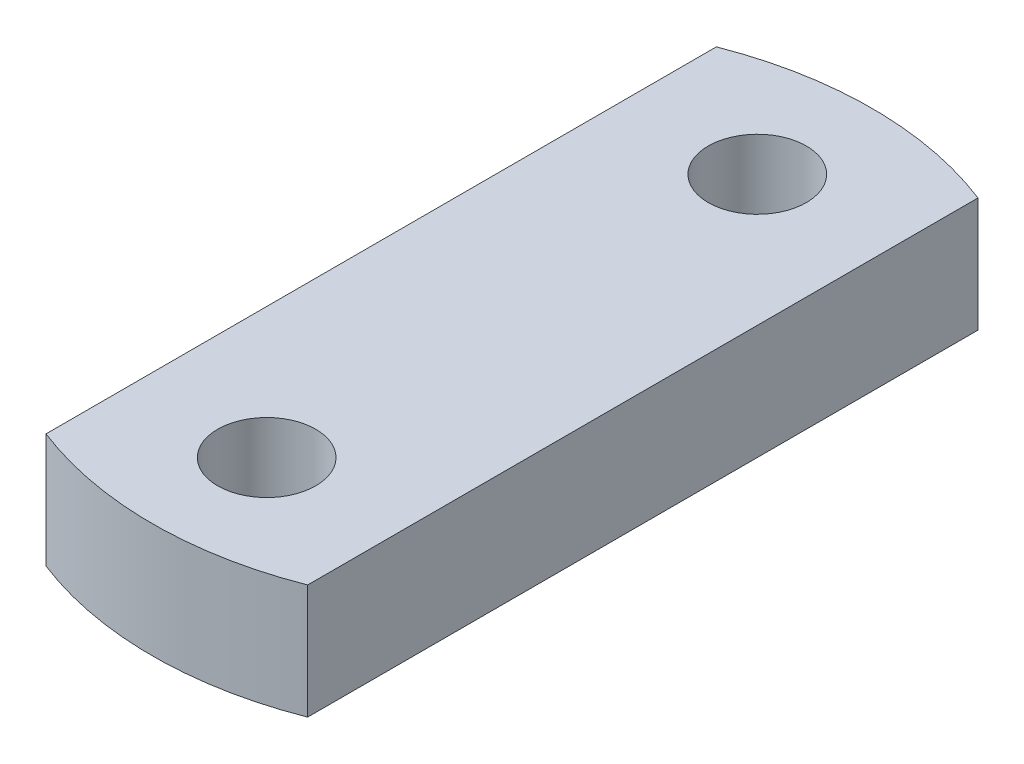
SolidWorks part; units mm, degrees
ref_plane "Front Plane" through (0, 0, 0) normal (0, 0, 1) x (1, 0, 0)
ref_plane "Top Plane" through (0, 0, 0) normal (0, 1, 0) x (1, 0, 0)
ref_plane "Right Plane" through (0, 0, 0) normal (1, 0, 0) x (0, 0, -1)
sketch "Sketch1" plane through (0, 0, 0) normal (0, 1, 0) x (1, 0, 0)
  line L0 (0, 145.8323) -> (0, -104.5554) construction
  line L1 (-208.2428, 0) -> (208.2428, 0) construction
  line L2 (-40, 102.4695) -> (-40, -102.4695)
  line L3 (40, 102.4695) -> (40, -102.4695)
  circle A0 centre (0, 75) radius 15
  circle A1 centre (0, -75) radius 15
  arc A2 (-40, -102.4695) -> (40, -102.4695) centre (0, 0) ccw
  arc A3 (40, 102.4695) -> (-40, 102.4695) centre (0, 0) ccw
  point P15 (-39.179, 115.3064)
  dimension "D3" = 30
  dimension "D4" = 220
  dimension "D1" = 150
  dimension "D2" = 75
  dimension "D5" = 80
  dimension "D6" = 40
extrude "Boss-Extrude1" add sketch "Sketch1" along normal blind 35
